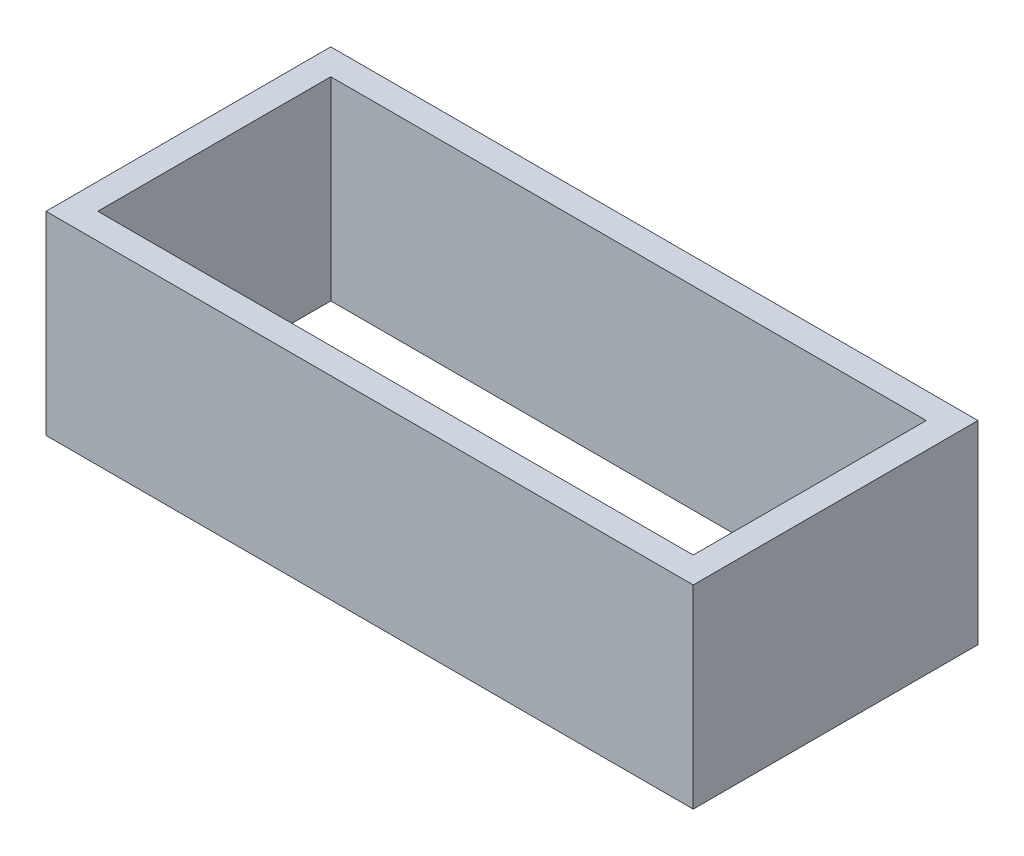
SolidWorks part; units mm, degrees
ref_plane "Front Plane" through (0, 0, 0) normal (0, 0, 1) x (1, 0, 0)
ref_plane "Top Plane" through (0, 0, 0) normal (0, 1, 0) x (1, 0, 0)
ref_plane "Right Plane" through (0, 0, 0) normal (1, 0, 0) x (0, 0, -1)
sketch "Sketch2" plane through (0, 0, 0) normal (0, 1, 0) x (1, 0, 0)
  line L5 (-50, -22) -> (50, -22)
  line L6 (-50, -22) -> (-50, 22)
  line L11 (-50, 22) -> (50, 22)
  line L12 (50, -22) -> (50, 22)
  line L13 (-50, -22) -> (50, 22) construction
  line L14 (-50, 22) -> (50, -22) construction
  line L15 (-46, 18) -> (46, 18)
  line L16 (-46, 18) -> (-46, -18)
  line L17 (-46, -18) -> (46, -18)
  line L18 (46, 18) -> (46, -18)
  line L19 (-46, 18) -> (46, -18) construction
  line L20 (-46, -18) -> (46, 18) construction
  point P0 (0, 0)
  point P6 (0, 0)
  dimension "D1" = 100
  dimension "D2" = 44
  dimension "D3" = 4
  dimension "D4" = 4
extrude "Boss-Extrude2" add sketch "Sketch2" along normal blind 30
ref_plane "Plane1" through (0, 0, 0) normal (0, 0, 1) x (1, 0, 0)
ref_plane "Plane2" through (0, 0, 0) normal (1, 0, 0) x (0, 0, -1)
sketch "Sketch4" plane through (0, 0, 0) normal (0, 0, 1) x (1, 0, 0)
  line L0 (0, 30) -> (0, 190)
  line L1 (-50, 30) -> (50, 30) construction
  line L2 (0, 30) -> (0, -130)
  line L3 (0, 30) -> (160, 30)
  line L4 (0, 30) -> (-160, 30)
  arc A0 (0, 190) -> (160, 30) centre (0, 30) cw
  arc A1 (0, -130) -> (160, 30) centre (0, 30) ccw
  arc A2 (0, -130) -> (-160, 30) centre (0, 30) cw
  arc A3 (-160, 30) -> (0, 190) centre (0, 30) cw
  dimension "D1" = 160
  dimension "D2" = 160
  dimension "D3" = 160
  dimension "D4" = 160
sketch "Sketch5" plane through (0, 0, 0) normal (1, 0, 0) x (0, 0, -1)
  line L0 (0, 30) -> (-160, 30)
  line L1 (0, 30) -> (0, -130) construction
  line L2 (0, 30) -> (0, 190) construction
  line L3 (0, 30) -> (160, 30)
  line L4 (0, 30) -> (0, 190)
  line L5 (0, 30) -> (0, -130)
  arc A0 (0, 190) -> (160, 30) centre (0, 30) cw
  arc A1 (0, 190) -> (-160, 30) centre (0, 30) ccw
  arc A2 (0, -130) -> (160, 30) centre (0, 30) ccw
  arc A3 (0, -130) -> (-160, 30) centre (0, 30) cw
  dimension "D1" = 160
  dimension "D2" = 160
  dimension "D3" = 160
